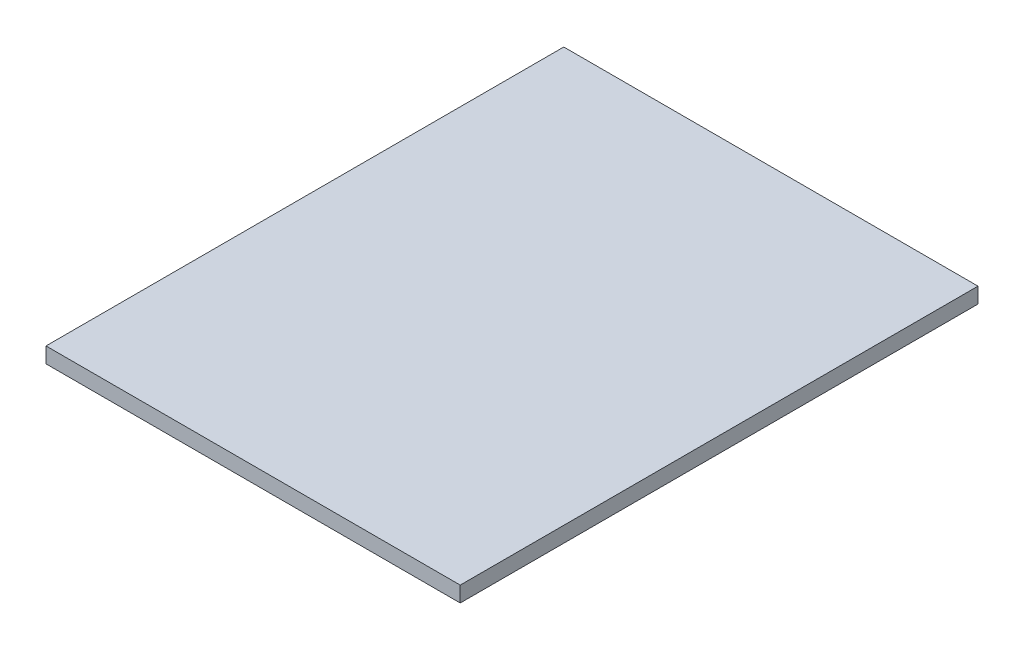
SolidWorks part; units mm, degrees
ref_plane "Front Plane" through (0, 0, 0) normal (0, 0, 1) x (1, 0, 0)
ref_plane "Top Plane" through (0, 0, 0) normal (0, 1, 0) x (1, 0, 0)
ref_plane "Right Plane" through (0, 0, 0) normal (1, 0, 0) x (0, 0, -1)
sketch "Sketch1" plane through (0, 0, 0) normal (0, 1, 0) x (1, 0, 0)
  line L1 (0.4, 10.5) -> (20.4, 10.5)
  line L2 (0.4, 10.5) -> (0.4, -14.5)
  line L3 (0.4, -14.5) -> (20.4, -14.5)
  line L4 (20.4, 10.5) -> (20.4, -14.5)
  dimension "D1" = 25
  dimension "D2" = 20
extrude "Boss-Extrude1" add sketch "Sketch1" along normal blind 0.75 contours L1 L4 L3 L2
